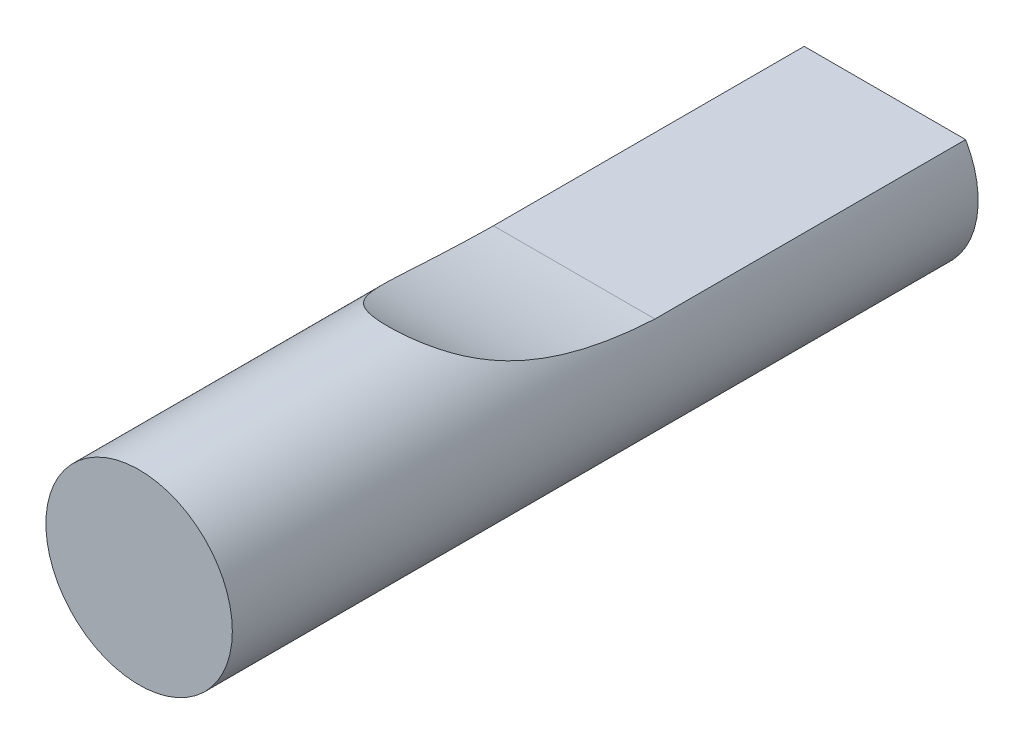
SolidWorks part; units mm, degrees
ref_plane "Plan de face" through (0, 0, 0) normal (0, 0, 1) x (1, 0, 0)
ref_plane "Plan de dessus" through (0, 0, 0) normal (0, 1, 0) x (1, 0, 0)
ref_plane "Plan de droite" through (0, 0, 0) normal (1, 0, 0) x (0, 0, -1)
sketch "Esquisse1" plane through (0, 0, 0) normal (0, 0, 1) x (1, 0, 0)
  line L0 (-1.299, 0.75) -> (1.299, 0.75)
  arc A0 (-1.299, 0.75) -> (1.299, 0.75) centre (0, 0) ccw
  dimension "D1" = 3
  dimension "D2" = 0.75
extrude "Boss.-Extru.1" add sketch "Esquisse1" along normal blind 5
sketch "Esquisse2" plane through (0, 0, 5) normal (0, 0, 1) x (1, 0, 0)
  circle A0 centre (0, 0) radius 1.5
  dimension "D1" = 3
extrude "Boss.-Extru.2" add sketch "Esquisse2" along normal blind 7
ref_plane "Plan1" through (1.5, 0, 0) normal (1, 0, 0) x (0, 0, -1)
sketch "Esquisse3" plane through (1.5, 0, 0) normal (1, 0, 0) x (0, 0, -1)
  line L0 (-5, 1.5) -> (-12, 1.5) construction
  line L1 (-12, 1.5) -> (-12, -1.5) construction
  line L2 (-8, 1.5) -> (-5, 1.5)
  line L3 (-5, 0.75) -> (-5, 1.5) construction
  line L4 (-5, 1.5) -> (-5, 0.75)
  spline S0 degree 2 poles (-8, 1.5) (-6.8945, 0.8118) (-5, 0.75) knots 0 0 0 0.697142 0.697142 0.697142
  point P0 (-5, 0.75)
  point P1 (-8, 1.5)
  point P10 (-5.6588, 0.827)
  dimension "D1" = 4
extrude "Enlèv. mat.-Extru.1" cut sketch "Esquisse3" against normal blind 3
